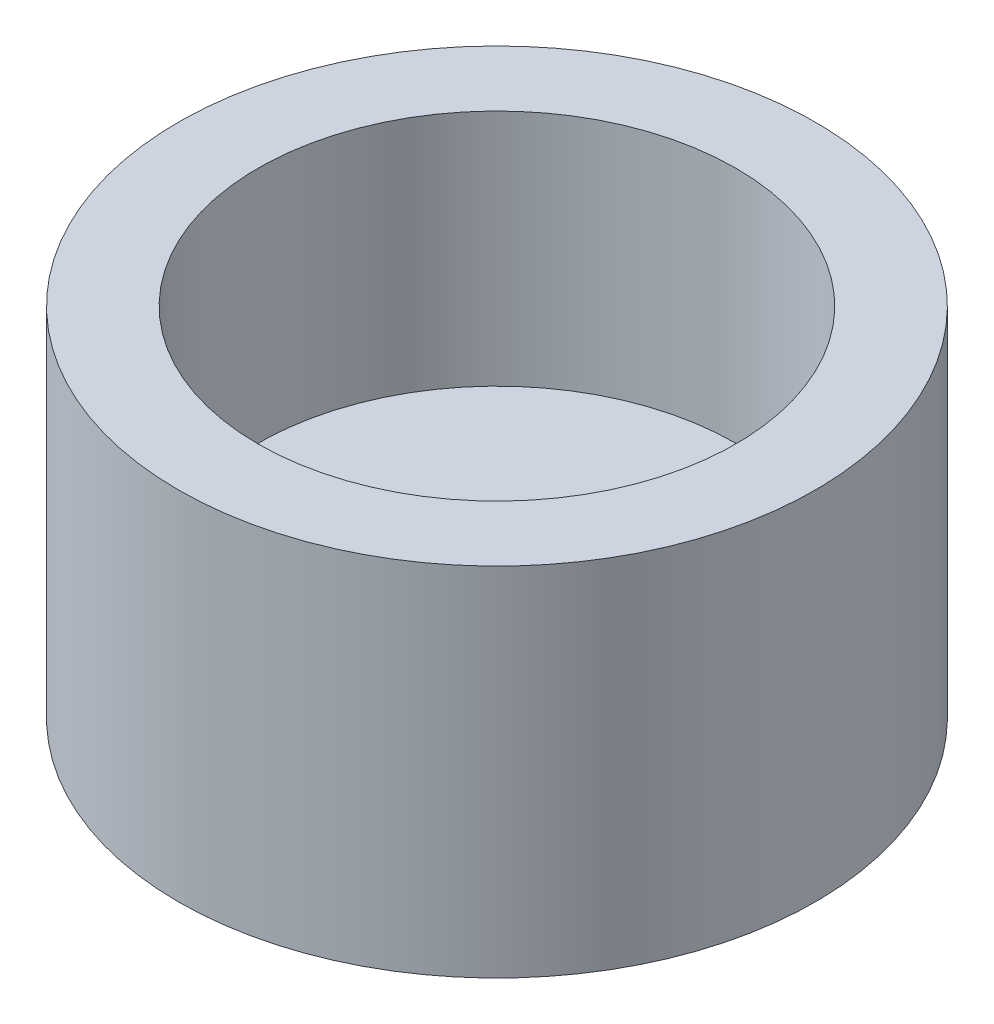
SolidWorks part; units mm, degrees
ref_plane "Plan de face" through (0, 0, 0) normal (0, 0, 1) x (1, 0, 0)
ref_plane "Plan de dessus" through (0, 0, 0) normal (0, 1, 0) x (1, 0, 0)
ref_plane "Plan de droite" through (0, 0, 0) normal (1, 0, 0) x (0, 0, -1)
sketch "Esquisse1" plane through (0, 0, 0) normal (0, 1, 0) x (1, 0, 0)
  circle A0 centre (0, 0) radius 25.4
extrude "Boss.-Extru.1" add sketch "Esquisse1" along normal blind 28.45
sketch "Esquisse2" plane through (0, 28.45, 0) normal (0, 1, 0) x (1, 0, 0)
  circle A0 centre (0, 0) radius 19.05
extrude "Enlèv. mat.-Extru.1" cut sketch "Esquisse2" against normal blind 19
